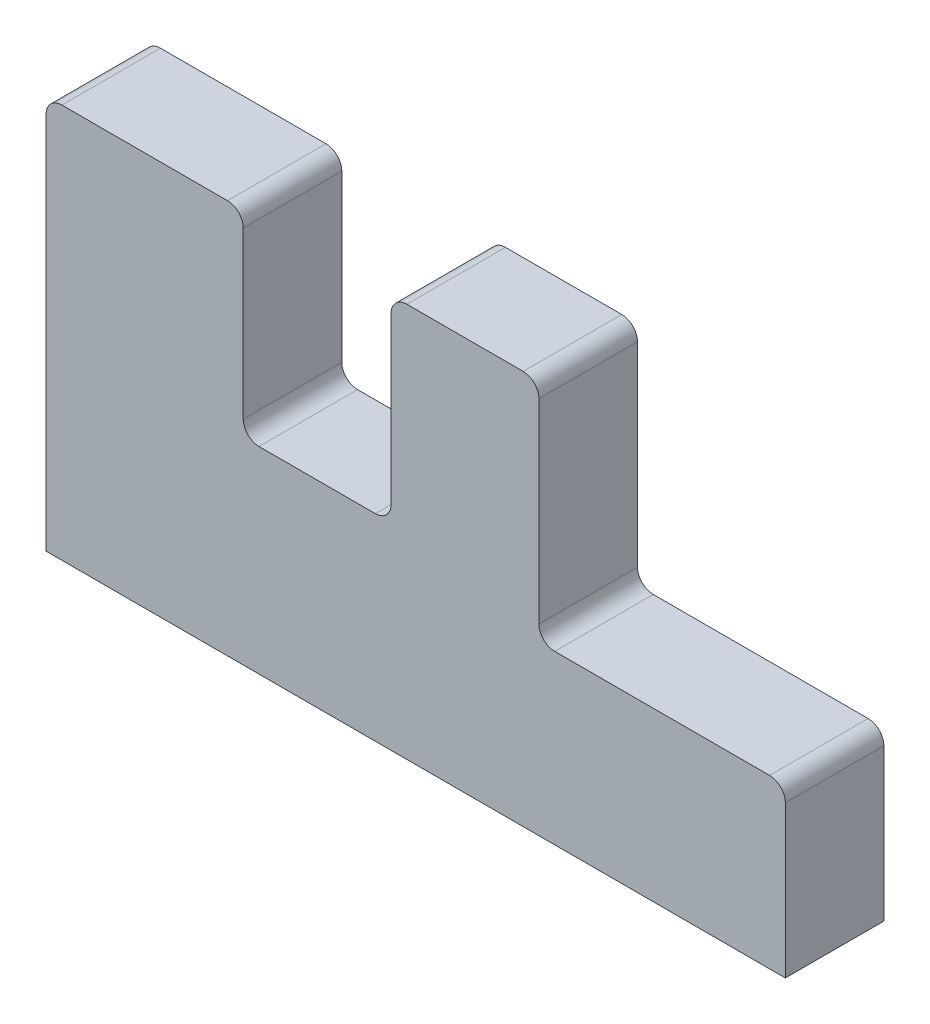
SolidWorks part; units mm, degrees
ref_plane "Front Plane" through (0, 0, 0) normal (0, 0, 1) x (1, 0, 0)
ref_plane "Top Plane" through (0, 0, 0) normal (0, 1, 0) x (1, 0, 0)
ref_plane "Right Plane" through (0, 0, 0) normal (1, 0, 0) x (0, 0, -1)
sketch "Sketch1" plane through (0, 0, 0) normal (0, 0, 1) x (1, 0, 0)
  line L0 (0, 0) -> (0, 2000)
  line L1 (0, 2000) -> (1000, 2000)
  line L2 (1000, 2000) -> (1000, 1000)
  line L3 (1000, 1000) -> (1750, 1000)
  line L4 (1750, 1000) -> (1750, 2000)
  line L5 (1750, 2000) -> (2500, 2000)
  line L6 (2500, 2000) -> (2500, 850)
  line L7 (2500, 850) -> (3750, 850)
  line L8 (3750, 850) -> (3750, 0)
  line L9 (3750, 0) -> (0, 0)
  dimension "D1" = 3750
  dimension "D2" = 2000
  dimension "D3" = 1000
  dimension "D4" = 1750
  dimension "D5" = 2500
  dimension "D6" = 850
  dimension "D7" = 1000
extrude "Boss-Extrude1" add sketch "Sketch1" along normal blind 500
fillet "Fillet1" radius 80 8 edges at (3750, 850, 250) (0, 2000, 250) (1000, 2000, 250) (1000, 1000, 250) (1750, 1000, 250) (1750, 2000, 250) (2500, 850, 250) (2500, 2000, 250)
